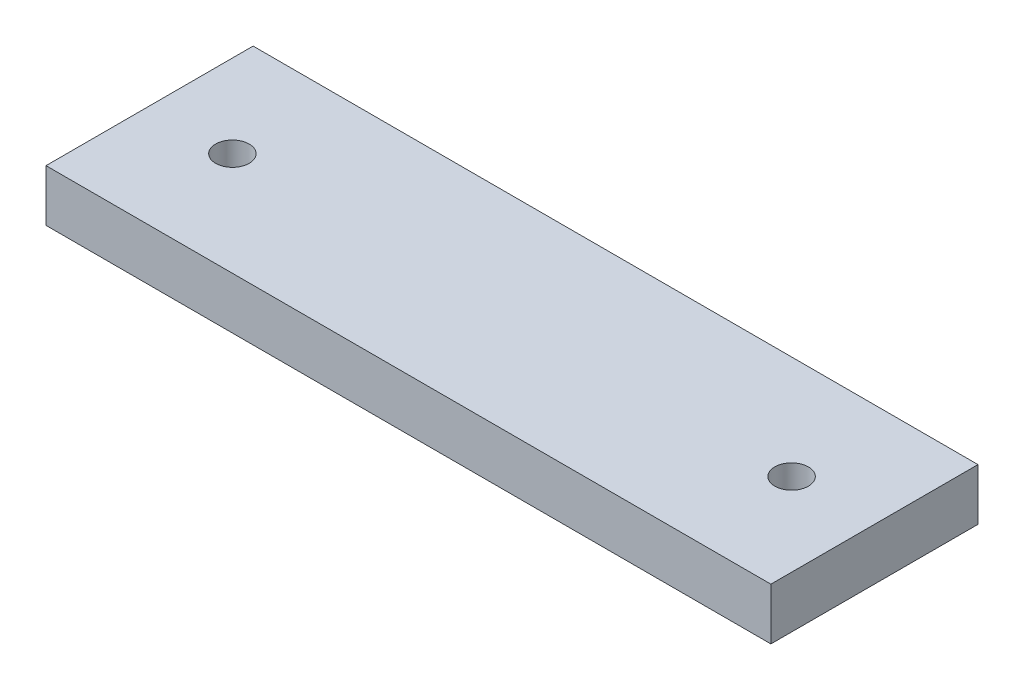
SolidWorks part; units mm, degrees
ref_plane "Front Plane" through (0, 0, 0) normal (0, 0, 1) x (1, 0, 0)
ref_plane "Top Plane" through (0, 0, 0) normal (0, 1, 0) x (1, 0, 0)
ref_plane "Right Plane" through (0, 0, 0) normal (1, 0, 0) x (0, 0, -1)
sketch "Sketch1" plane through (0, 0, 0) normal (0, 1, 0) x (1, 0, 0)
  line L1 (-22.225, -6.35) -> (22.225, -6.35)
  line L2 (-22.225, -6.35) -> (-22.225, 6.35)
  line L3 (-22.225, 6.35) -> (22.225, 6.35)
  line L4 (22.225, -6.35) -> (22.225, 6.35)
  circle A0 centre (-17.145, 0) radius 1.0287
  circle A1 centre (17.145, 0) radius 1.0287
  point P0 (0, 0)
  point P6 (-17.145, 0)
  point P11 (17.145, 0)
  dimension "D3" = 2.0574
  dimension "D1" = 12.7
  dimension "D2" = 44.45
extrude "Boss-Extrude1" add sketch "Sketch1" along normal blind 3.175
